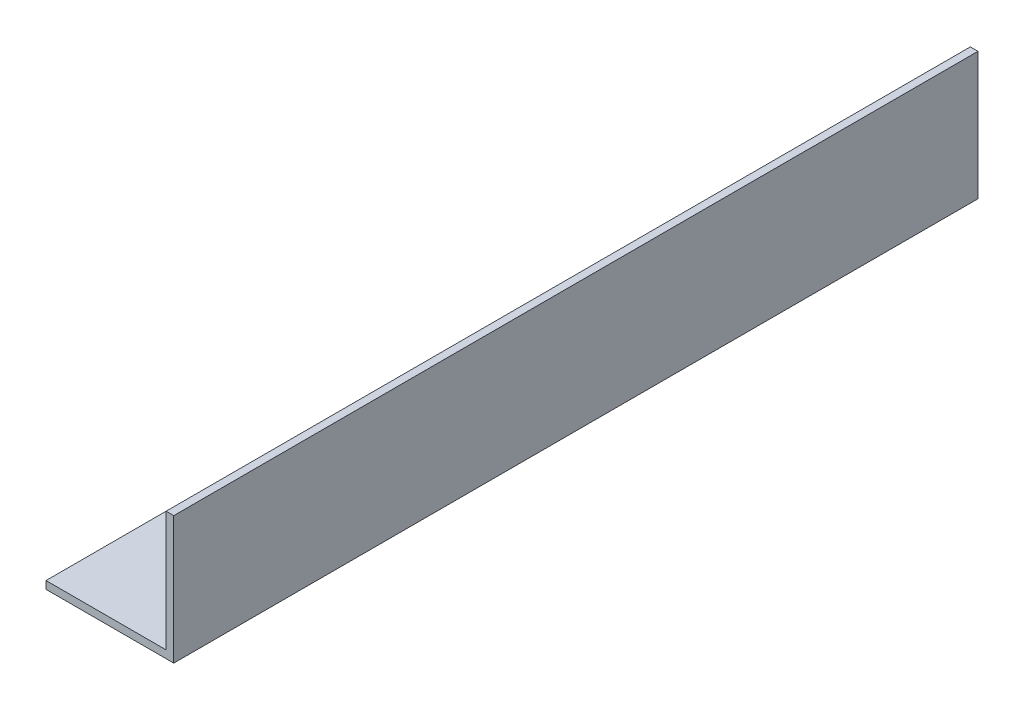
SolidWorks part; units mm, degrees
ref_plane "Front Plane" through (0, 0, 0) normal (0, 0, 1) x (1, 0, 0)
ref_plane "Top Plane" through (0, 0, 0) normal (0, 1, 0) x (1, 0, 0)
ref_plane "Right Plane" through (0, 0, 0) normal (1, 0, 0) x (0, 0, -1)
sketch "Sketch1" plane through (0, 0, 0) normal (0, 0, 1) x (1, 0, 0)
  line L0 (-50, 0) -> (0, 0)
  line L1 (0, 0) -> (0, 50)
  line L2 (0, 50) -> (-3, 50)
  line L3 (-3, 50) -> (-3, 3)
  line L4 (-3, 3) -> (-50, 3)
  line L5 (-50, 0) -> (-50, 3)
  line L6 (-1.5, 50) -> (0, 50) construction
  line L7 (-50, 1.5) -> (-50, 0) construction
  dimension "Vert" = 50
  dimension "Horz" = 50
  dimension "Thickness" = 3
sketch "Sketch2" plane through (0, 0, 0) normal (1, 0, 0) x (0, 0, -1)
  line L0 (-304.8, 0) -> (304.8, 0) construction
  point P0 (-292.608, 0)
  point P4 (0, 0)
  point P5 (292.608, 0)
  dimension "Length" = 609.6
  dimension "D1" = 12.192
  dimension "D2" = 12.192
sketch "Sketch3" plane through (0, 0, 0) normal (0, 0, 1) x (1, 0, 0)
  line L0 (-50, 0) -> (0, 0) construction
  line L1 (0, 0) -> (0, 50) construction
  line L2 (0, 50) -> (-3, 50) construction
  line L3 (-3, 50) -> (-3, 3) construction
  line L4 (-3, 3) -> (-50, 3) construction
  line L5 (-50, 0) -> (-50, 3) construction
  line L6 (-50, 0) -> (0, 0)
  line L7 (0, 0) -> (0, 50)
  line L8 (0, 50) -> (-3, 50)
  line L9 (-3, 50) -> (-3, 3)
  line L10 (-3, 3) -> (-50, 3)
  line L11 (-50, 0) -> (-50, 3)
extrude "Boss-Extrude1" add sketch "Sketch3" along normal blind 10 and the other way up to vertex (304.8 mm away) other way up to point (0, 0, -304.8)
sketch "Sketch4" plane through (0, 0, 0) normal (0, 1, 0) x (1, 0, 0)
  line L0 (-26.5, -10) -> (-26.5, 304.8) construction
  line L1 (-3, -10) -> (-50, -10) construction
  line L2 (-3, 304.8) -> (-50, 304.8) construction
  line L3 (-50, 147.4) -> (-3, 147.4) construction
  line L4 (-50, 304.8) -> (-50, -10) construction
  line L5 (-3, 304.8) -> (-3, -10) construction
  circle A0 centre (-37, 156.19) radius 2.585
  circle A1 centre (-16, 156.19) radius 2.585
  circle A2 centre (-37, 184.19) radius 2.585
  circle A3 centre (-16, 184.19) radius 2.585
  circle A4 centre (-37, 110.61) radius 2.585
  circle A5 centre (-16, 110.61) radius 2.585
  circle A6 centre (-16, 138.61) radius 2.585
  circle A7 centre (-37, 138.61) radius 2.585
  dimension "D1" = 5.17
  dimension "D3" = 5.17
  dimension "D2" = 10.5
  dimension "D4" = 28
  dimension "D5" = 8.79
extrude "Cut-Extrude1" cut sketch "Sketch4" along normal through all
equation "\"D1@Sketch2\"=\"Length@Sketch2\"*.02"
equation "\"D2@Sketch2\"=\"D1@Sketch2\""
